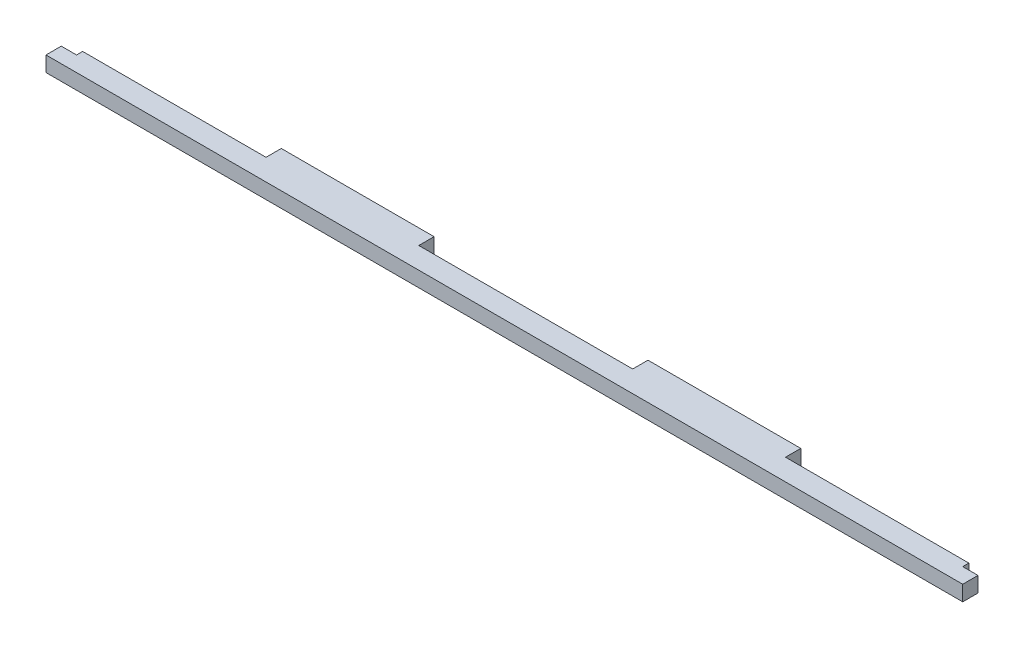
SolidWorks part; units mm, degrees
ref_plane "前视基准面" through (0, 0, 0) normal (0, 0, 1) x (1, 0, 0)
ref_plane "上视基准面" through (0, 0, 0) normal (0, 1, 0) x (1, 0, 0)
ref_plane "右视基准面" through (0, 0, 0) normal (1, 0, 0) x (0, 0, -1)
sketch "草图1" plane through (0, 0, 0) normal (0, 1, 0) x (1, 0, 0)
  line L0 (115, 7) -> (185, 7)
  line L1 (0, 0) -> (300, 0)
  line L2 (0, 0) -> (0, 5)
  line L3 (5, 7) -> (65, 7)
  line L4 (300, 0) -> (300, 5)
  line L5 (235, 7) -> (295, 7)
  line L6 (65, 7) -> (65, 12)
  line L7 (65, 12) -> (115, 12)
  line L8 (115, 7) -> (115, 12)
  line L9 (0, 5) -> (5, 5)
  line L10 (185, 7) -> (185, 12)
  line L11 (185, 12) -> (235, 12)
  line L12 (235, 7) -> (235, 12)
  line L13 (5, 5) -> (5, 7)
  line L14 (295, 7) -> (295, 5)
  line L15 (295, 5) -> (300, 5)
  dimension "D2" = 300
  dimension "D3" = 50
  dimension "D4" = 5
  dimension "D5" = 5
  dimension "D6" = 50
  dimension "D7" = 5
  dimension "D9" = 5
  dimension "D10" = 2
  dimension "D11" = 2
extrude "凸台-拉伸1" add sketch "草图1" along normal blind 5
